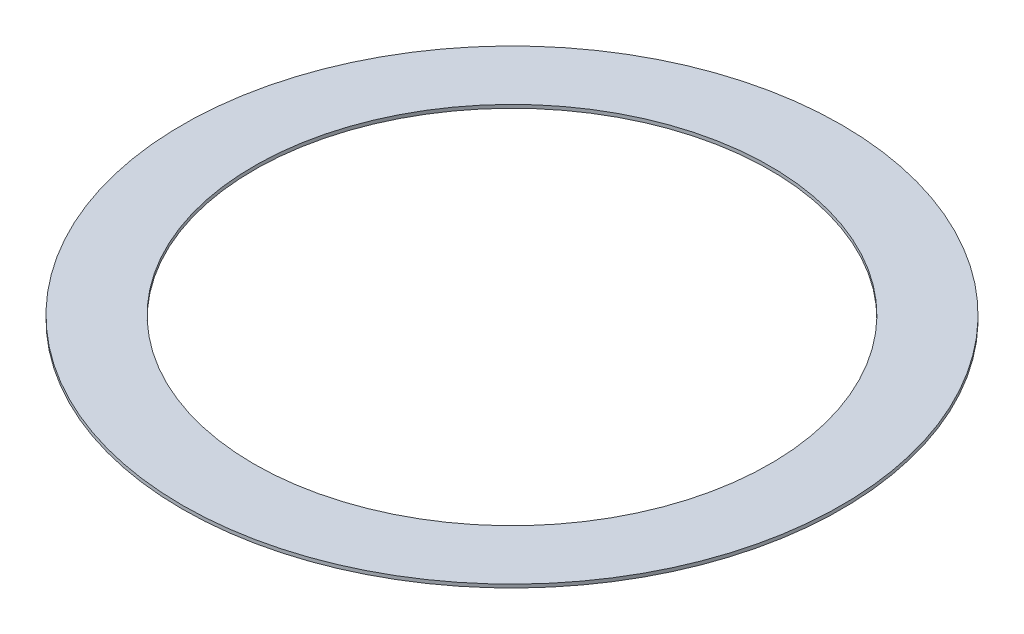
SolidWorks part; units mm, degrees
ref_plane "Front Plane" through (0, 0, 0) normal (0, 0, 1) x (1, 0, 0)
ref_plane "Top Plane" through (0, 0, 0) normal (0, 1, 0) x (1, 0, 0)
ref_plane "Right Plane" through (0, 0, 0) normal (1, 0, 0) x (0, 0, -1)
sketch "Sketch1" plane through (0, 0, 0) normal (0, 1, 0) x (1, 0, 0)
  circle A0 centre (0, 0) radius 228.8876
  circle A1 centre (0, 0) radius 292.3377
extrude "Boss-Extrude1" add sketch "Sketch1" along normal blind 3
